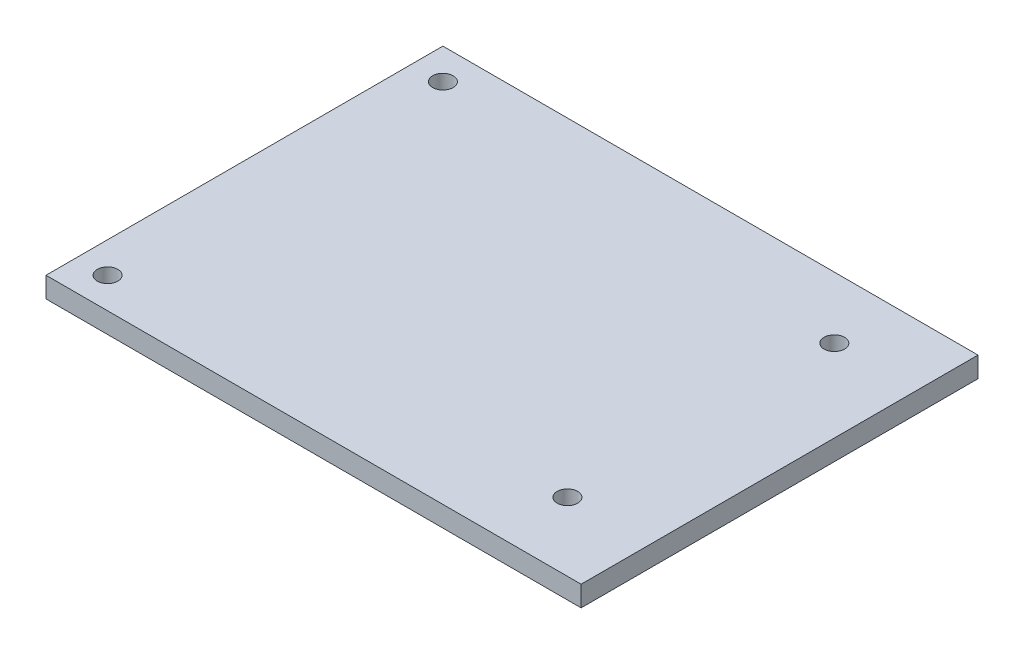
SolidWorks part; units mm, degrees
ref_plane "Front Plane" through (0, 0, 0) normal (0, 0, 1) x (1, 0, 0)
ref_plane "Top Plane" through (0, 0, 0) normal (0, 1, 0) x (1, 0, 0)
ref_plane "Right Plane" through (0, 0, 0) normal (1, 0, 0) x (0, 0, -1)
sketch "Sketch1" plane through (0, 0, 0) normal (0, 1, 0) x (1, 0, 0)
  line L1 (-39.1, -29) -> (39.1, -29)
  line L2 (-39.1, -29) -> (-39.1, 29)
  line L3 (-39.1, 29) -> (39.1, 29)
  line L4 (39.1, -29) -> (39.1, 29)
  line L5 (-39.1, -29) -> (39.1, 29) construction
  line L6 (-39.1, 29) -> (39.1, -29) construction
  point P0 (0, 0)
  dimension "D1" = 58
  dimension "D2" = 78.2
extrude "Boss-Extrude1" add sketch "Sketch1" along normal blind 3
sketch "Sketch2" plane through (0, 3, 0) normal (0, 1, 0) x (1, 0, 0)
  line L0 (-39.1, -29) -> (39.1, -29) construction
  line L1 (-39.1, 29) -> (-39.1, -29) construction
  circle A0 centre (-34.6, 24.5) radius 1.5
  circle A1 centre (-34.6, -24.5) radius 1.5
  dimension "D1" = 49
  dimension "D2" = 3
  dimension "D3" = 3
  dimension "D5" = 4.5
  dimension "D6" = 4.5
  dimension "D4" = 4.5
extrude "Cut-Extrude1" cut sketch "Sketch2" against normal blind 3
sketch "Sketch3" plane through (0, 3, 0) normal (0, 1, 0) x (1, 0, 0)
  line L1 (39.1, 29) -> (-39.1, 29) construction
  line L2 (39.1, -29) -> (39.1, 29) construction
  circle A0 centre (27.1, 20) radius 1.5
  circle A1 centre (27.1, -19) radius 1.5
  dimension "D1" = 39
  dimension "D2" = 3
  dimension "D3" = 3
  dimension "D4" = 9
  dimension "D5" = 12
  dimension "D6" = 12
extrude "Cut-Extrude2" cut sketch "Sketch3" against normal blind 3
